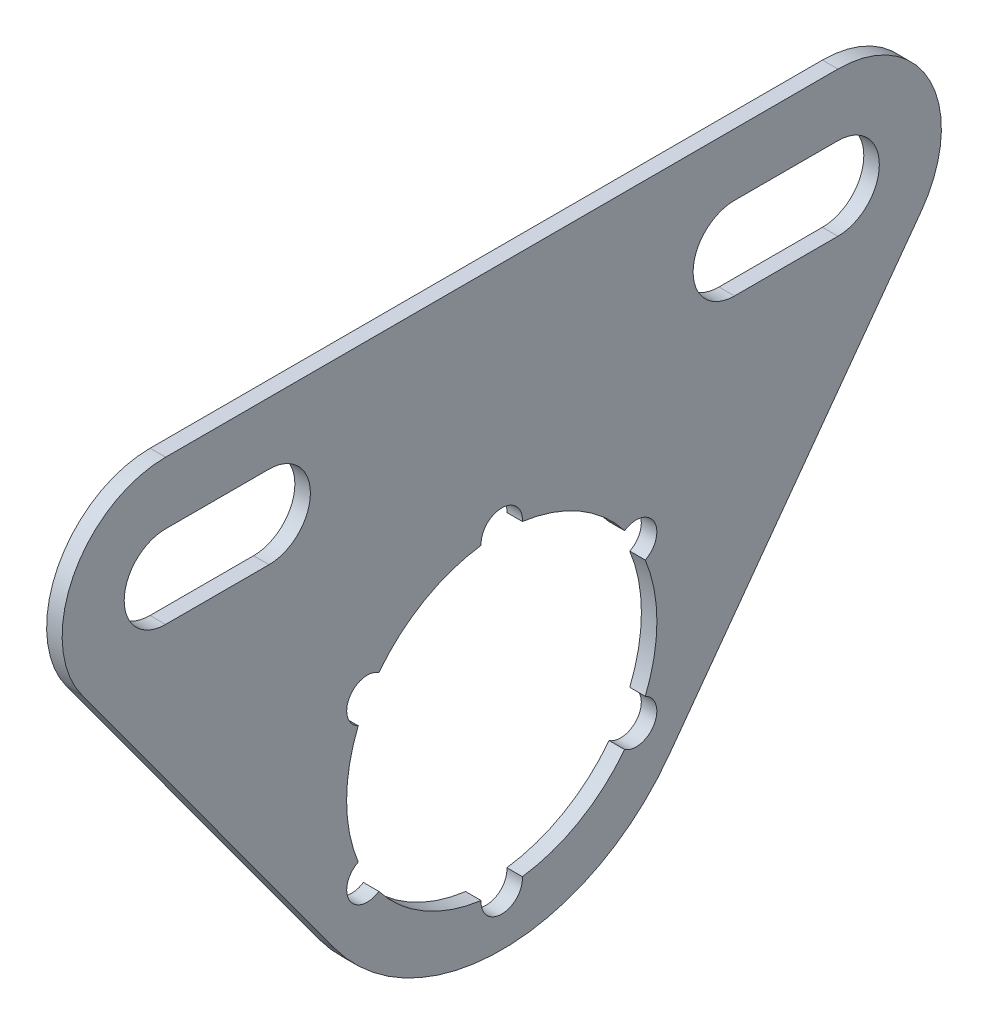
SolidWorks part; units mm, degrees
ref_plane "Front Plane" through (0, 0, 0) normal (0, 0, 1) x (1, 0, 0)
ref_plane "Top Plane" through (0, 0, 0) normal (0, 1, 0) x (1, 0, 0)
ref_plane "Right Plane" through (0, 0, 0) normal (1, 0, 0) x (0, 0, -1)
sketch "Sketch1" plane through (0, 0, 0) normal (1, 0, 0) x (0, 0, -1)
  line L0 (-65, 55) -> (65, 55) construction
  line L30 (-65, 75) -> (65, 75)
  line L39 (-65, 55) -> (-45, 55) construction
  line L44 (-81.1436, 43.1939) -> (-32.2872, -23.6122)
  line L45 (-65, 63) -> (-45, 63)
  line L46 (81.1436, 43.1939) -> (32.2872, -23.6122)
  line L47 (-65, 47) -> (-45, 47)
  line L48 (65, 55) -> (45, 55) construction
  line L49 (65, 47) -> (45, 47)
  line L50 (65, 63) -> (45, 63)
  arc A50 (-65, 75) -> (-81.1436, 43.1939) centre (-65, 55) ccw
  arc A51 (81.1436, 43.1939) -> (65, 75) centre (65, 55) ccw
  arc A55 (-32.2872, -23.6122) -> (32.2872, -23.6122) centre (0, 0) ccw
  arc A56 (81.1436, 43.1939) -> (65, 75) centre (65, 55) ccw
  arc A57 (-32.2872, -23.6122) -> (32.2872, -23.6122) centre (0, 0) ccw
  circle A58 centre (0, 0) radius 20
  arc A59 (-27.7454, 11.4103) -> (-27.7454, -11.4103) centre (0, 0) ccw
  arc A60 (-65, 63) -> (-65, 47) centre (-65, 55) ccw
  arc A61 (-45, 47) -> (-45, 63) centre (-45, 55) ccw
  arc A62 (65, 47) -> (65, 63) centre (65, 55) ccw
  arc A63 (45, 63) -> (45, 47) centre (45, 55) ccw
  circle A64 centre (0, 30) radius 4
  circle A65 centre (25.9808, 15) radius 4
  arc A66 (-27.7454, 11.4103) -> (-27.7454, -11.4103) centre (0, 0) ccw
  circle A67 centre (25.9808, -15) radius 4
  arc A68 (-27.7454, 11.4103) -> (-27.7454, -11.4103) centre (0, 0) ccw
  circle A69 centre (0, -30) radius 4
  arc A70 (-27.7454, 11.4103) -> (-27.7454, -11.4103) centre (0, 0) ccw
  circle A71 centre (-25.9808, -15) radius 4
  arc A72 (-27.7454, 11.4103) -> (-27.7454, -11.4103) centre (0, 0) ccw
  circle A73 centre (-25.9808, 15) radius 4
  arc A74 (-27.7454, 11.4103) -> (-27.7454, -11.4103) centre (0, 0) ccw
  arc A75 (-3.9911, 29.7333) -> (-23.7543, 18.3231) centre (0, 0) ccw
  arc A76 (-3.9911, 29.7333) -> (-23.7543, 18.3231) centre (0, 0) ccw
  arc A77 (-3.9911, 29.7333) -> (-23.7543, 18.3231) centre (0, 0) ccw
  arc A78 (-3.9911, 29.7333) -> (-23.7543, 18.3231) centre (0, 0) ccw
  arc A79 (-3.9911, 29.7333) -> (-23.7543, 18.3231) centre (0, 0) ccw
  arc A80 (-3.9911, 29.7333) -> (-23.7543, 18.3231) centre (0, 0) ccw
  arc A81 (23.7543, 18.3231) -> (3.9911, 29.7333) centre (0, 0) ccw
  arc A82 (23.7543, 18.3231) -> (3.9911, 29.7333) centre (0, 0) ccw
  arc A83 (23.7543, 18.3231) -> (3.9911, 29.7333) centre (0, 0) ccw
  arc A84 (23.7543, 18.3231) -> (3.9911, 29.7333) centre (0, 0) ccw
  arc A85 (23.7543, 18.3231) -> (3.9911, 29.7333) centre (0, 0) ccw
  arc A86 (23.7543, 18.3231) -> (3.9911, 29.7333) centre (0, 0) ccw
  arc A87 (27.7454, -11.4103) -> (27.7454, 11.4103) centre (0, 0) ccw
  arc A88 (27.7454, -11.4103) -> (27.7454, 11.4103) centre (0, 0) ccw
  arc A89 (27.7454, -11.4103) -> (27.7454, 11.4103) centre (0, 0) ccw
  arc A90 (27.7454, -11.4103) -> (27.7454, 11.4103) centre (0, 0) ccw
  arc A91 (27.7454, -11.4103) -> (27.7454, 11.4103) centre (0, 0) ccw
  arc A92 (27.7454, -11.4103) -> (27.7454, 11.4103) centre (0, 0) ccw
  arc A93 (3.9911, -29.7333) -> (23.7543, -18.3231) centre (0, 0) ccw
  arc A94 (3.9911, -29.7333) -> (23.7543, -18.3231) centre (0, 0) ccw
  arc A95 (3.9911, -29.7333) -> (23.7543, -18.3231) centre (0, 0) ccw
  arc A96 (3.9911, -29.7333) -> (23.7543, -18.3231) centre (0, 0) ccw
  arc A97 (3.9911, -29.7333) -> (23.7543, -18.3231) centre (0, 0) ccw
  arc A98 (3.9911, -29.7333) -> (23.7543, -18.3231) centre (0, 0) ccw
  arc A99 (-23.7543, -18.3231) -> (-3.9911, -29.7333) centre (0, 0) ccw
  arc A100 (-23.7543, -18.3231) -> (-3.9911, -29.7333) centre (0, 0) ccw
  arc A101 (-23.7543, -18.3231) -> (-3.9911, -29.7333) centre (0, 0) ccw
  arc A102 (-23.7543, -18.3231) -> (-3.9911, -29.7333) centre (0, 0) ccw
  arc A103 (-23.7543, -18.3231) -> (-3.9911, -29.7333) centre (0, 0) ccw
  arc A104 (-23.7543, -18.3231) -> (-3.9911, -29.7333) centre (0, 0) ccw
  point P2 (-55, 55)
  point P12 (-229.6848, 87.7398)
  point P18 (55, 55)
  point P19 (-164.51, 87.7398)
  point P29 (0, 55)
  point P47 (0, 0)
  dimension "D1" = 20
  dimension "D2" = 40
  dimension "D3" = 55
  dimension "D4" = 45
  dimension "D5" = 20
  dimension "D11" = 8
  dimension "D7" = 8
  dimension "D9" = 40
  dimension "D10" = 60
  dimension "D6" = 45
  dimension "D8" = 6
extrude "Boss-Extrude2" add sketch "Sketch1" along normal blind 3 contours L44 A55 L46 A51 L30 A50 A99 A71 A59 A73 A75 A64 A81 A65 A87 A67 A93 A69 A63 L50 A62 L49 A61 L47 A60 L45
